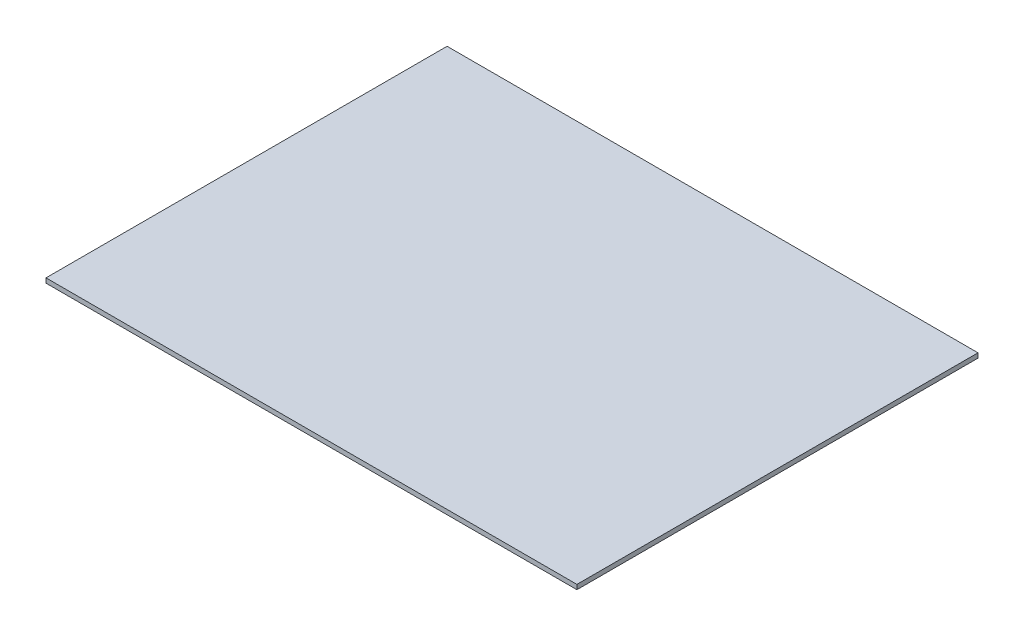
SolidWorks part; units mm, degrees
ref_plane "Front Plane" through (0, 0, 0) normal (0, 0, 1) x (1, 0, 0)
ref_plane "Top Plane" through (0, 0, 0) normal (0, 1, 0) x (1, 0, 0)
ref_plane "Right Plane" through (0, 0, 0) normal (1, 0, 0) x (0, 0, -1)
sketch "Sketch1" plane through (0, 0, 0) normal (0, 1, 0) x (1, 0, 0)
  line L1 (0, 0) -> (229, 0)
  line L2 (0, 0) -> (0, 173)
  line L3 (0, 173) -> (229, 173)
  line L4 (229, 0) -> (229, 173)
  dimension "D1" = 229
  dimension "D2" = 173
extrude "Boss-Extrude1" add sketch "Sketch1" along normal blind 2
